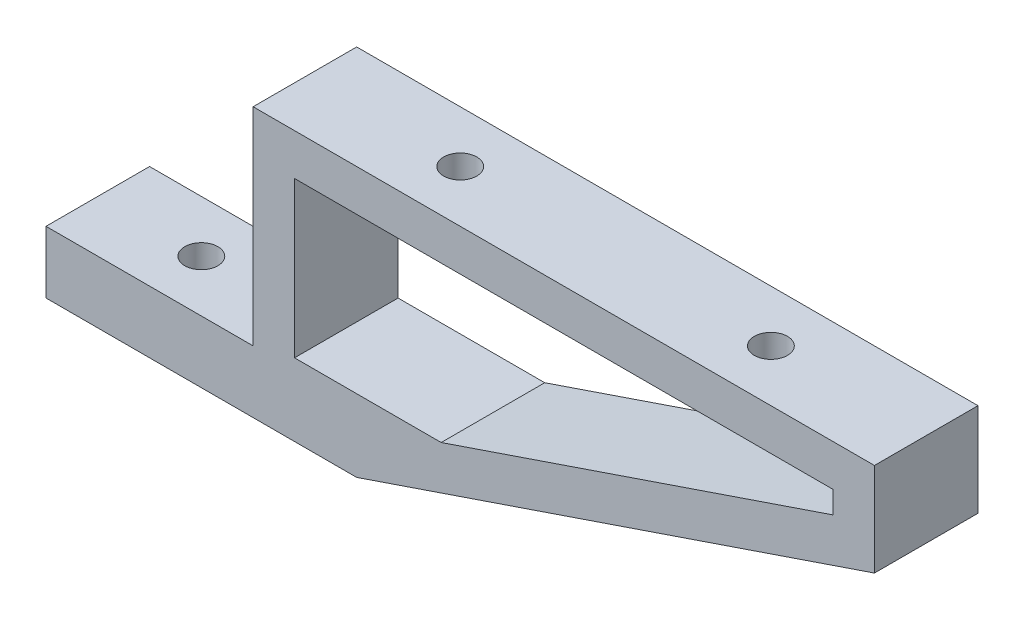
SolidWorks part; units mm, degrees
ref_plane "前视基准面" through (0, 0, 0) normal (0, 0, 1) x (1, 0, 0)
ref_plane "上视基准面" through (0, 0, 0) normal (0, 1, 0) x (1, 0, 0)
ref_plane "右视基准面" through (0, 0, 0) normal (1, 0, 0) x (0, 0, -1)
other "Configuration Table"
sketch "草图1" plane through (0, 0, 0) normal (0, 0, 1) x (1, 0, 0)
  line L0 (0, 0) -> (20, 0)
  line L1 (20, 0) -> (20, 20)
  line L2 (20, 20) -> (80, 20)
  line L4 (30, -6) -> (0, -6)
  line L5 (0, -6) -> (0, 0)
  line L6 (80, 20) -> (80, 11)
  line L7 (80, 11) -> (30, -6)
  line L8 (24, 16) -> (24, 1)
  line L9 (24, 1) -> (38.1621, 1)
  line L10 (38.1621, 1) -> (76, 13.8649)
  line L11 (76, 13.8649) -> (76, 16)
  line L12 (76, 16) -> (24, 16)
  point P10 (59.3241, 9.1166)
  point P14 (80, 10.3768)
  point P15 (80, 11)
  point P16 (30.6318, -4)
  dimension "D1" = 20
  dimension "D2" = 6
  dimension "D3" = 20
  dimension "D4" = 4
  dimension "D5" = 4
  dimension "D6" = 4
  dimension "D7" = 4
  dimension "D8" = 7
  dimension "D9" = 60
  dimension "D10" = 9
  dimension "D11" = 30
extrude "凸台-拉伸1" add sketch "草图1" along normal blind 10
sketch "草图2" plane through (0, 0, 0) normal (0, 1, 0) x (1, 0, 0)
  line L0 (10, 0) -> (10, -50000) construction
  line L1 (20, 0) -> (0, 0) construction
  line L2 (0, -5) -> (50000, -5) construction
  line L3 (0, -10) -> (0, 0) construction
  circle A0 centre (10, -5) radius 1.6
  point P4 (10, 0)
  point P9 (0, -5)
  dimension "D1" = 3.2
extrude "切除-拉伸1" cut sketch "草图2" against normal through all
sketch "草图3" plane through (0, 20, 0) normal (0, 1, 0) x (1, 0, 0)
  line L0 (20, -5) -> (50020, -5) construction
  line L1 (20, -10) -> (20, 0) construction
  line L2 (80, -10) -> (80, 0) construction
  circle A0 centre (65, -5) radius 1.6
  circle A1 centre (35, -5) radius 1.6
  point P4 (20, -5)
  dimension "D1" = 30
  dimension "D2" = 15
  dimension "D3" = 3.2
extrude "切除-拉伸2" cut sketch "草图3" against normal up to surface (4 mm away) up to face at (50, 16, 5)
